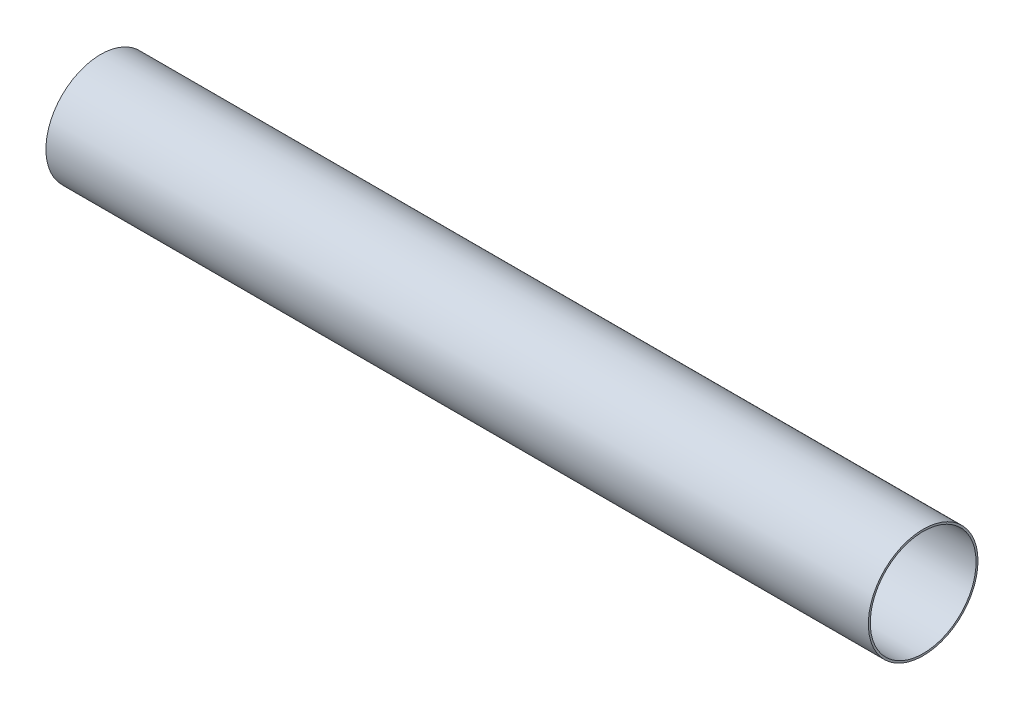
SolidWorks part; units mm, degrees
ref_plane "Front Plane" through (0, 0, 0) normal (0, 0, 1) x (1, 0, 0)
ref_plane "Top Plane" through (0, 0, 0) normal (0, 1, 0) x (1, 0, 0)
ref_plane "Right Plane" through (0, 0, 0) normal (1, 0, 0) x (0, 0, -1)
sketch "Sketch1" plane through (0, 0, 0) normal (1, 0, 0) x (0, 0, -1)
  circle A0 centre (0, 0) radius 49.022
  circle A1 centre (0, 0) radius 50.8
  dimension "D1" = 101.6
  dimension "D2" = 1.778
extrude "Boss-Extrude1" add sketch "Sketch1" along normal blind 762
